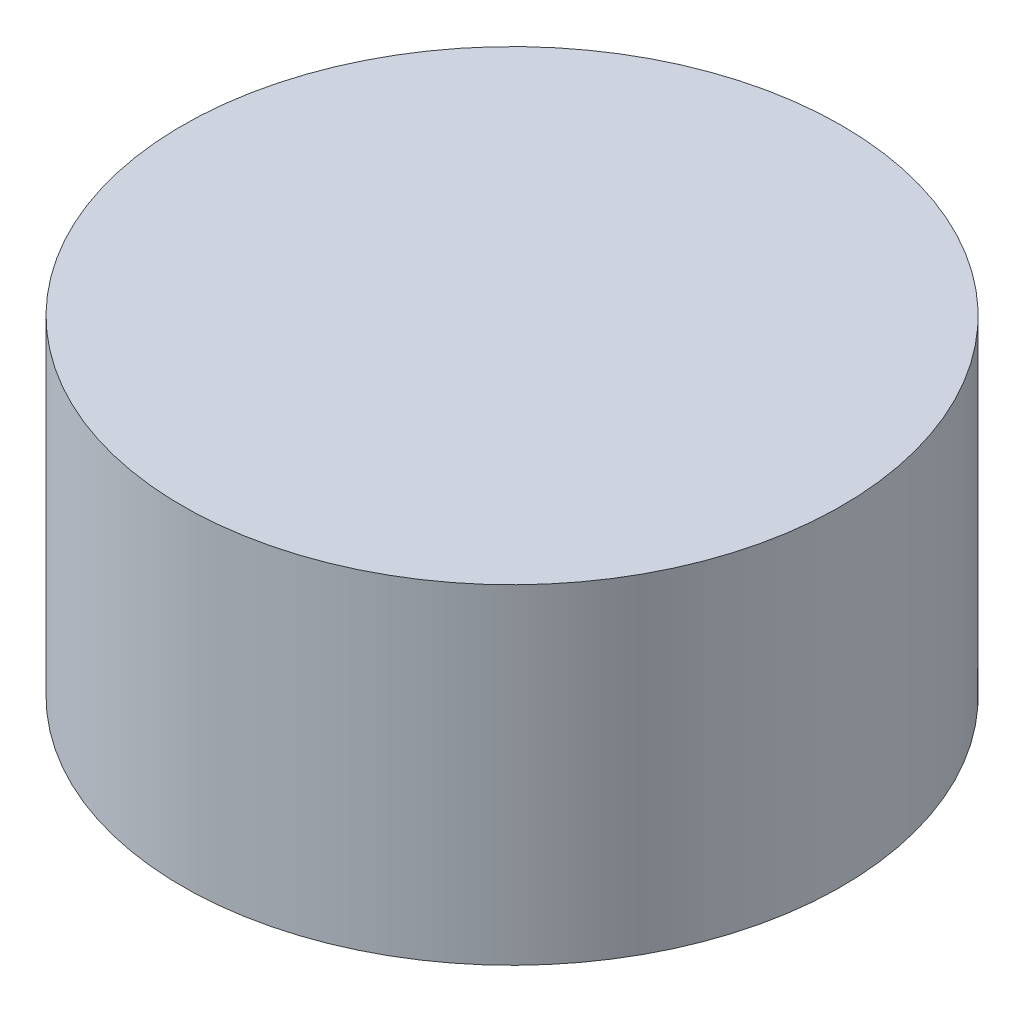
SolidWorks part; units mm, degrees
ref_plane "Front Plane" through (0, 0, 0) normal (0, 0, 1) x (1, 0, 0)
ref_plane "Top Plane" through (0, 0, 0) normal (0, 1, 0) x (1, 0, 0)
ref_plane "Right Plane" through (0, 0, 0) normal (1, 0, 0) x (0, 0, -1)
sketch "Sketch1" plane through (0, 0, 0) normal (0, 1, 0) x (1, 0, 0)
  circle A0 centre (0, 0) radius 38.1
extrude "Boss-Extrude1" add sketch "Sketch1" along normal blind 38.1
